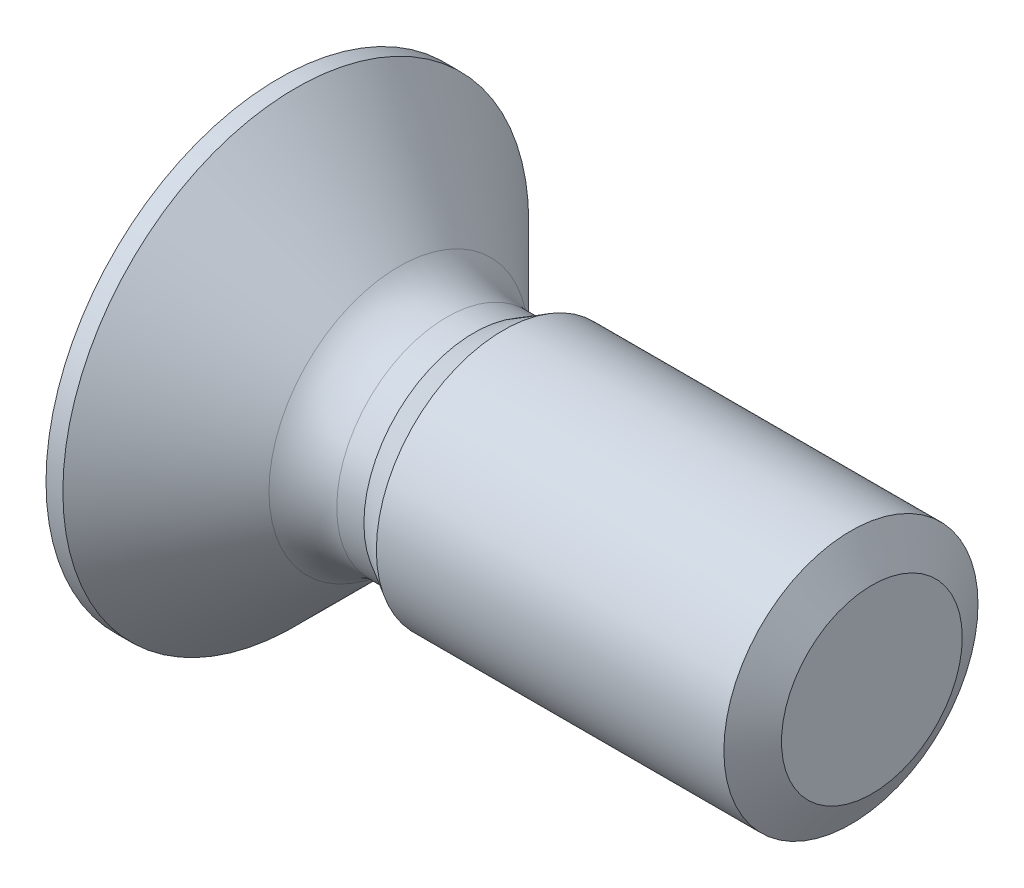
SolidWorks part; units mm, degrees
revolve "基体-旋转" add sketch "草图1" angle 360 about L0
sketch "草图1" plane through (0, 0, 0) normal (0, 0, 1) x (1, 0, 0)
  line L0 (0, 0) -> (4.4175, 0) construction
  line L1 (0, 0) -> (0, 2.75)
  line L2 (0, 2.75) -> (0.199, 2.75)
  line L3 (0.199, 2.75) -> (1.4157, 1.5333)
  line L4 (1.9814, 1.299) -> (2.3019, 1.299)
  line L5 (2.3019, 1.299) -> (2.65, 1.5)
  line L6 (2.65, 1.5) -> (7, 1.5)
  line L7 (7, 1.5) -> (7, 0)
  line L8 (0, 0) -> (7, 0)
  arc A0 (1.9814, 1.299) -> (1.4157, 1.5333) centre (1.9814, 2.099) cw
  point P12 (1.65, 1.299)
  dimension "D2" = 0.8
  dimension "D1" = 2.598
  dimension "d" = 3
  dimension "dk" = 5.5
  dimension "k" = 1.65
  dimension "D5" = 45
  dimension "a" = 1
  dimension "l" = 7
  dimension "D8" = 30
cosmetic thread "装饰螺纹线2" parameters "D1"=4.35, "D2"=2.5
material "AISI 304"
ref_plane "前视" through (0, 0, 0) normal (0, 0, 1) x (1, 0, 0)
ref_plane "上视" through (0, 0, 0) normal (0, 1, 0) x (1, 0, 0)
ref_plane "右视" through (0, 0, 0) normal (1, 0, 0) x (0, 0, -1)
sketch "尺寸草图" plane through (0, 0, 0) normal (0, 0, 1) x (1, 0, 0)
  line L0 (0, 0) -> (7, 0)
  point P3 (1.65, 0)
  point P4 (1, 0)
  point P5 (3, 0)
  point P6 (5.5, 0)
  point P7 (3.8, 0)
  point P8 (3.5943, 0)
  point P9 (6.2, 0)
  point P10 (4.9, 0)
  point P11 (6.5, 0)
  dimension "d" = 3
  dimension "dk" = 5.5
  dimension "k" = 1.65
  dimension "a" = 1
  dimension "l" = 7
  dimension "r" = 0.8
  dimension "m" = 3.2
  dimension "h" = 2.1
  dimension "p" = 0.5
sketch "草图2" plane through (0, 0, 0) normal (0, 0, 1) x (1, 0, 0)
  line L0 (6.7527, 1.5) -> (7.2527, 1.5)
  line L1 (7.2527, 1.5) -> (7, 1.067)
  line L2 (7, 1.067) -> (6.7527, 1.5)
  line L3 (7, -1.5) -> (7, 1.5) construction
  line L6 (0, 0) -> (-0.4315, 0) construction
  dimension "D1" = 0.5
  dimension "D2" = 0.433
  dimension "D3" = 1.5
  dimension "D4" = 60
revolve "切除-旋转1" cut sketch "草图2" angle 360 about L6
pattern_linear "阵列(线性)1" [suppressed] count 9 spacing 0.5 along (1, 0, 0)
sketch "草图3" plane through (0, 0, 0) normal (-1, 0, 0) x (0, 0, 1)
  line L0 (0, 0) -> (1.6329, 0) construction
  line L1 (0, 0) -> (0, 0.8499) construction
  line L2 (-1.6, 0.25) -> (1.6, 0.25)
  line L3 (-1.6, 0.25) -> (-1.6, -0.25)
  line L4 (-1.6, -0.25) -> (1.6, -0.25)
  line L5 (1.6, 0.25) -> (1.6, -0.25)
  dimension "m" = 3.2
  dimension "D1" = 0.5
ref_plane "基准面1" through (2.1, 0, 0) normal (-1, 0, 0) x (0, 0, 1)
sketch "草图4" plane through (2.1, 0, 0) normal (-1, 0, 0) x (0, 0, 1)
  point P0 (0, 0)
loft "切除-放样1" cut profiles "草图3", "草图4"
pattern_circular "阵列(圆周)1" count 2 every 90 about axis through (0, 0, 0) along (1, 0, 0) of "切除-放样1"
equation "\"l@草图1\" = \"l@尺寸草图\""
equation "\"k@草图1\" = \"k@尺寸草图\""
equation "\"a@草图1\" = \"a@尺寸草图\""
equation "\"d@草图1\" = \"d@尺寸草图\""
equation "\"dk@草图1\" = \"dk@尺寸草图\""
equation "\"D2@草图1\" = \"r@尺寸草图\""
equation "\"m@草图3\" = \"m@尺寸草图\""
equation "\"h@基准面1\" = \"h@尺寸草图\""
equation "\"D3@阵列(线性)1\" = \"p@尺寸草图\""
equation "\"D3@草图2\" = \"d@草图1\" / 2"
equation "\"D1@装饰螺纹线2\" = \"l@草图1\" - \"k@草图1\" - \"a@草图1\""
equation "\"D2@装饰螺纹线2\" = \"d@尺寸草图\"- \"p@尺寸草图\""
equation "\"D1@阵列(线性)1\" = (  \"l@草图1\" - \"k@草图1\" - \"a@草图1\" )  / \"p@尺寸草图\""
equation "\"D1@草图3\" = \"p@尺寸草图\""
equation "\"D1@草图1\" = \"d@尺寸草图\"*0.866"
equation "\"D2@草图2\" = \"p@尺寸草图\"*0.866"
equation "\"D1@草图2\" = \"p@尺寸草图\""
